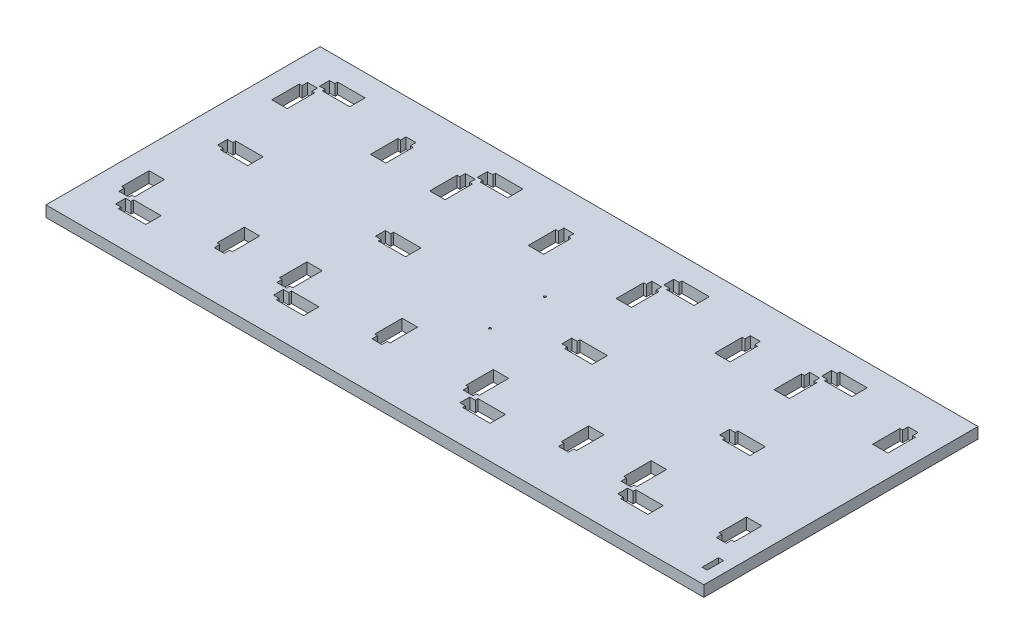
SolidWorks part; units mm, degrees
ref_plane "Front Plane" through (0, 0, 0) normal (0, 0, 1) x (1, 0, 0)
ref_plane "Top Plane" through (0, 0, 0) normal (0, 1, 0) x (1, 0, 0)
ref_plane "Right Plane" through (0, 0, 0) normal (1, 0, 0) x (0, 0, -1)
sketch "Sketch1" plane through (0, 0, 0) normal (0, 1, 0) x (1, 0, 0)
  line L0 (300, 0) -> (300, -250) construction
  line L1 (0, 0) -> (600, 0)
  line L2 (0, 0) -> (0, -250)
  line L3 (0, -250) -> (600, -250)
  line L4 (600, 0) -> (600, -250)
  line L5 (36, -113) -> (61, -113)
  line L6 (36, -20) -> (61, -20)
  line L8 (36, -34) -> (61, -34)
  line L9 (61, -20) -> (61, -34)
  line L11 (36, -127) -> (61, -127)
  line L12 (61, -113) -> (61, -127)
  line L13 (36, -206) -> (61, -206)
  line L15 (36, -220) -> (61, -220)
  line L16 (61, -206) -> (61, -220)
  line L19 (20, -39) -> (20, -64)
  line L20 (20, -64) -> (34, -64)
  line L21 (34, -39) -> (34, -64)
  line L22 (108, -37.0948) -> (108, -62.0948)
  line L23 (108, -62.0948) -> (122, -62.0948)
  line L24 (122, -37.0948) -> (122, -62.0948)
  line L25 (20, -176) -> (34, -176)
  line L26 (20, -176) -> (20, -201)
  line L28 (34, -176) -> (34, -203)
  line L29 (108, -177.0915) -> (122, -177.0915)
  line L30 (108, -177.0915) -> (108, -202.0915)
  line L32 (122, -177.0915) -> (122, -202.0915)
  line L61 (144, 0) -> (144, -250) construction
  line L62 (280, 0) -> (280, -250) construction
  line L75 (0, -20) -> (600, -20) construction
  line L92 (0, -220) -> (600, -220) construction
  line L93 (164, 0) -> (164, -250) construction
  line L150 (580, 0) -> (580, -250) construction
  line L151 (320, 0) -> (320, -250) construction
  line L152 (460, 0) -> (460, -250) construction
  line L153 (440, 0) -> (440, -250) construction
  line L194 (20, 0) -> (20, -250) construction
  line L263 (36, -20) -> (36, -22.5)
  line L272 (36, -22.5) -> (31, -22.5)
  line L273 (31, -22.5) -> (31, -31.5)
  line L274 (31, -31.5) -> (36, -31.5)
  line L275 (36, -31.5) -> (36, -34)
  line L276 (20, -39) -> (22.5, -39)
  line L277 (22.5, -39) -> (22.5, -34)
  line L278 (22.5, -34) -> (31.5, -34)
  line L279 (31.5, -34) -> (31.5, -39)
  line L280 (31.5, -39) -> (34, -39)
  line L281 (108, -37.0948) -> (110.5, -37.0948)
  line L282 (110.5, -37.0948) -> (110.5, -32.0948)
  line L283 (110.5, -32.0948) -> (119.5, -32.0948)
  line L284 (119.5, -32.0948) -> (119.5, -37.0948)
  line L285 (119.5, -37.0948) -> (122, -37.0948)
  line L286 (36, -113) -> (36, -115.5)
  line L287 (36, -115.5) -> (31, -115.5)
  line L288 (31, -115.5) -> (31, -124.5)
  line L289 (31, -124.5) -> (36, -124.5)
  line L290 (36, -124.5) -> (36, -127)
  line L291 (20, -201) -> (22.5, -201)
  line L292 (22.5, -201) -> (22.5, -206)
  line L293 (22.5, -206) -> (31.5, -206)
  line L294 (31.5, -206) -> (31.5, -203)
  line L295 (31.5, -203) -> (34, -203)
  line L296 (36, -206) -> (36, -208.5)
  line L297 (36, -208.5) -> (31, -208.5)
  line L298 (31, -208.5) -> (31, -217.5)
  line L299 (31, -217.5) -> (36, -217.5)
  line L300 (36, -217.5) -> (36, -220)
  line L301 (108, -202.0915) -> (110.5, -202.0915)
  line L302 (110.5, -202.0915) -> (110.5, -207.0915)
  line L303 (110.5, -207.0915) -> (119.5, -207.0915)
  line L304 (119.5, -207.0915) -> (119.5, -202.0915)
  line L305 (119.5, -202.0915) -> (122, -202.0915)
  line L306 (179.9626, -31.5) -> (179.9626, -34)
  line L307 (179.9626, -34) -> (204.9626, -34)
  line L308 (204.9626, -20) -> (204.9626, -34)
  line L309 (179.9626, -20) -> (204.9626, -20)
  line L310 (179.9626, -20) -> (179.9626, -22.5)
  line L311 (179.9626, -22.5) -> (174.9626, -22.5)
  line L312 (174.9626, -22.5) -> (174.9626, -31.5)
  line L313 (174.9626, -31.5) -> (179.9626, -31.5)
  line L314 (263.4626, -37.0948) -> (265.9626, -37.0948)
  line L315 (265.9626, -37.0948) -> (265.9626, -62.0948)
  line L316 (251.9626, -62.0948) -> (265.9626, -62.0948)
  line L317 (251.9626, -37.0948) -> (251.9626, -62.0948)
  line L318 (251.9626, -37.0948) -> (254.4626, -37.0948)
  line L319 (254.4626, -37.0948) -> (254.4626, -32.0948)
  line L320 (254.4626, -32.0948) -> (263.4626, -32.0948)
  line L321 (263.4626, -32.0948) -> (263.4626, -37.0948)
  line L322 (175.4626, -39) -> (177.9626, -39)
  line L323 (177.9626, -39) -> (177.9626, -64)
  line L324 (163.9626, -64) -> (177.9626, -64)
  line L325 (163.9626, -39) -> (163.9626, -64)
  line L326 (163.9626, -39) -> (166.4626, -39)
  line L327 (166.4626, -39) -> (166.4626, -34)
  line L328 (166.4626, -34) -> (175.4626, -34)
  line L329 (175.4626, -34) -> (175.4626, -39)
  line L330 (179.9626, -124.5) -> (179.9626, -127)
  line L331 (179.9626, -127) -> (204.9626, -127)
  line L332 (204.9626, -113) -> (204.9626, -127)
  line L333 (179.9626, -113) -> (204.9626, -113)
  line L334 (179.9626, -113) -> (179.9626, -115.5)
  line L335 (179.9626, -115.5) -> (174.9626, -115.5)
  line L336 (174.9626, -115.5) -> (174.9626, -124.5)
  line L337 (174.9626, -124.5) -> (179.9626, -124.5)
  line L338 (263.4626, -202.0915) -> (265.9626, -202.0915)
  line L339 (265.9626, -177.0915) -> (265.9626, -202.0915)
  line L340 (251.9626, -177.0915) -> (265.9626, -177.0915)
  line L341 (251.9626, -177.0915) -> (251.9626, -202.0915)
  line L342 (251.9626, -202.0915) -> (254.4626, -202.0915)
  line L343 (254.4626, -202.0915) -> (254.4626, -207.0915)
  line L344 (254.4626, -207.0915) -> (263.4626, -207.0915)
  line L345 (263.4626, -207.0915) -> (263.4626, -202.0915)
  line L346 (175.4626, -203) -> (177.9626, -203)
  line L347 (177.9626, -176) -> (177.9626, -203)
  line L348 (163.9626, -176) -> (177.9626, -176)
  line L349 (163.9626, -176) -> (163.9626, -201)
  line L350 (163.9626, -201) -> (166.4626, -201)
  line L351 (166.4626, -201) -> (166.4626, -206)
  line L352 (166.4626, -206) -> (175.4626, -206)
  line L353 (175.4626, -206) -> (175.4626, -203)
  line L354 (179.9626, -217.5) -> (179.9626, -220)
  line L355 (179.9626, -220) -> (204.9626, -220)
  line L356 (204.9626, -206) -> (204.9626, -220)
  line L357 (179.9626, -206) -> (204.9626, -206)
  line L358 (179.9626, -206) -> (179.9626, -208.5)
  line L359 (179.9626, -208.5) -> (174.9626, -208.5)
  line L360 (174.9626, -208.5) -> (174.9626, -217.5)
  line L361 (174.9626, -217.5) -> (179.9626, -217.5)
  line L474 (350, -31.5) -> (350, -34)
  line L478 (350, -34) -> (375, -34)
  line L479 (585.3518, -222) -> (590, -222)
  line L480 (585.3518, -222) -> (585.3518, -237)
  line L481 (585.3518, -237) -> (590, -237)
  line L482 (590, -222) -> (590, -237)
  line L483 (375, -20) -> (375, -34)
  line L484 (350, -20) -> (375, -20)
  line L485 (350, -20) -> (350, -22.5)
  line L486 (350, -22.5) -> (345, -22.5)
  line L487 (345, -22.5) -> (345, -31.5)
  line L488 (345, -31.5) -> (350, -31.5)
  line L489 (433.5, -37.0948) -> (436, -37.0948)
  line L490 (436, -37.0948) -> (436, -62.0948)
  line L491 (422, -62.0948) -> (436, -62.0948)
  line L492 (422, -37.0948) -> (422, -62.0948)
  line L493 (422, -37.0948) -> (424.5, -37.0948)
  line L494 (424.5, -37.0948) -> (424.5, -32.0948)
  line L495 (424.5, -32.0948) -> (433.5, -32.0948)
  line L496 (433.5, -32.0948) -> (433.5, -37.0948)
  line L497 (345.5, -39) -> (348, -39)
  line L498 (348, -39) -> (348, -64)
  line L499 (334, -64) -> (348, -64)
  line L500 (334, -39) -> (334, -64)
  line L501 (334, -39) -> (336.5, -39)
  line L502 (336.5, -39) -> (336.5, -34)
  line L503 (336.5, -34) -> (345.5, -34)
  line L504 (345.5, -34) -> (345.5, -39)
  line L505 (350, -124.5) -> (350, -127)
  line L506 (350, -127) -> (375, -127)
  line L507 (375, -113) -> (375, -127)
  line L508 (350, -113) -> (375, -113)
  line L509 (350, -113) -> (350, -115.5)
  line L510 (350, -115.5) -> (345, -115.5)
  line L511 (345, -115.5) -> (345, -124.5)
  line L512 (345, -124.5) -> (350, -124.5)
  line L513 (433.5, -202.0915) -> (436, -202.0915)
  line L514 (436, -177.0915) -> (436, -202.0915)
  line L515 (422, -177.0915) -> (436, -177.0915)
  line L516 (422, -177.0915) -> (422, -202.0915)
  line L517 (422, -202.0915) -> (424.5, -202.0915)
  line L518 (424.5, -202.0915) -> (424.5, -207.0915)
  line L519 (424.5, -207.0915) -> (433.5, -207.0915)
  line L520 (433.5, -207.0915) -> (433.5, -202.0915)
  line L521 (345.5, -203) -> (348, -203)
  line L522 (348, -176) -> (348, -203)
  line L523 (334, -176) -> (348, -176)
  line L524 (334, -176) -> (334, -201)
  line L525 (334, -201) -> (336.5, -201)
  line L526 (336.5, -201) -> (336.5, -206)
  line L527 (336.5, -206) -> (345.5, -206)
  line L528 (345.5, -206) -> (345.5, -203)
  line L529 (350, -217.5) -> (350, -220)
  line L530 (350, -220) -> (375, -220)
  line L531 (375, -206) -> (375, -220)
  line L532 (350, -206) -> (375, -206)
  line L533 (350, -206) -> (350, -208.5)
  line L534 (350, -208.5) -> (345, -208.5)
  line L535 (345, -208.5) -> (345, -217.5)
  line L536 (345, -217.5) -> (350, -217.5)
  line L537 (489.4626, -203) -> (491.9626, -203)
  line L538 (491.9626, -176) -> (491.9626, -203)
  line L539 (477.9626, -176) -> (491.9626, -176)
  line L540 (477.9626, -176) -> (477.9626, -201)
  line L541 (477.9626, -201) -> (480.4626, -201)
  line L542 (480.4626, -201) -> (480.4626, -206)
  line L543 (480.4626, -206) -> (489.4626, -206)
  line L544 (489.4626, -206) -> (489.4626, -203)
  line L545 (493.9626, -217.5) -> (493.9626, -220)
  line L546 (493.9626, -220) -> (518.9626, -220)
  line L547 (518.9626, -206) -> (518.9626, -220)
  line L548 (493.9626, -206) -> (518.9626, -206)
  line L549 (493.9626, -206) -> (493.9626, -208.5)
  line L550 (493.9626, -208.5) -> (488.9626, -208.5)
  line L551 (488.9626, -208.5) -> (488.9626, -217.5)
  line L552 (488.9626, -217.5) -> (493.9626, -217.5)
  line L553 (577.4626, -202.0915) -> (579.9626, -202.0915)
  line L554 (579.9626, -177.0915) -> (579.9626, -202.0915)
  line L555 (565.9626, -177.0915) -> (579.9626, -177.0915)
  line L556 (565.9626, -177.0915) -> (565.9626, -202.0915)
  line L557 (565.9626, -202.0915) -> (568.4626, -202.0915)
  line L558 (568.4626, -202.0915) -> (568.4626, -207.0915)
  line L559 (568.4626, -207.0915) -> (577.4626, -207.0915)
  line L560 (577.4626, -207.0915) -> (577.4626, -202.0915)
  line L561 (493.9626, -124.5) -> (493.9626, -127)
  line L562 (493.9626, -127) -> (518.9626, -127)
  line L563 (518.9626, -113) -> (518.9626, -127)
  line L564 (493.9626, -113) -> (518.9626, -113)
  line L565 (493.9626, -113) -> (493.9626, -115.5)
  line L566 (493.9626, -115.5) -> (488.9626, -115.5)
  line L567 (488.9626, -115.5) -> (488.9626, -124.5)
  line L568 (488.9626, -124.5) -> (493.9626, -124.5)
  line L569 (489.4626, -39) -> (491.9626, -39)
  line L570 (491.9626, -39) -> (491.9626, -64)
  line L571 (477.9626, -64) -> (491.9626, -64)
  line L572 (477.9626, -39) -> (477.9626, -64)
  line L573 (477.9626, -39) -> (480.4626, -39)
  line L574 (480.4626, -39) -> (480.4626, -34)
  line L575 (480.4626, -34) -> (489.4626, -34)
  line L576 (489.4626, -34) -> (489.4626, -39)
  line L577 (493.9626, -31.5) -> (493.9626, -34)
  line L578 (493.9626, -34) -> (518.9626, -34)
  line L579 (518.9626, -20) -> (518.9626, -34)
  line L580 (493.9626, -20) -> (518.9626, -20)
  line L581 (493.9626, -20) -> (493.9626, -22.5)
  line L582 (493.9626, -22.5) -> (488.9626, -22.5)
  line L583 (488.9626, -22.5) -> (488.9626, -31.5)
  line L584 (488.9626, -31.5) -> (493.9626, -31.5)
  line L585 (577.4626, -37.0948) -> (579.9626, -37.0948)
  line L586 (579.9626, -37.0948) -> (579.9626, -62.0948)
  line L587 (565.9626, -62.0948) -> (579.9626, -62.0948)
  line L588 (565.9626, -37.0948) -> (565.9626, -62.0948)
  line L589 (565.9626, -37.0948) -> (568.4626, -37.0948)
  line L590 (568.4626, -37.0948) -> (568.4626, -32.0948)
  line L591 (568.4626, -32.0948) -> (577.4626, -32.0948)
  line L592 (577.4626, -32.0948) -> (577.4626, -37.0948)
  circle A0 centre (300, -95) radius 1
  circle A1 centre (300, -145) radius 1
  point P27 (108, -49.5948)
  point P67 (109.25, -202.0915)
  point P263 (300, -120)
  dimension "D54" = 2
  dimension "D55" = 2
  dimension "D1" = 250
  dimension "D2" = 600
  dimension "D3" = 25
  dimension "D4" = 14
  dimension "D7" = 79
  dimension "D8" = 79
  dimension "D9" = 20
  dimension "D10" = 14
  dimension "D11" = 25
  dimension "D12" = 14
  dimension "D13" = 25
  dimension "D14" = 20
  dimension "D15" = 5
  dimension "D16" = 74
  dimension "D17" = 2
  dimension "D18" = 2.5
  dimension "D19" = 25
  dimension "D20" = 14
  dimension "D21" = 14
  dimension "D22" = 25
  dimension "D23" = 14
  dimension "D24" = 74
  dimension "D25" = 10
  dimension "D26" = 14
  dimension "D27" = 25
  dimension "D28" = 36
  dimension "D29" = 25
  dimension "D30" = 36
  dimension "D31" = 49
  dimension "D32" = 20
  dimension "D33" = 36
  dimension "D34" = 2.5
  dimension "D35" = 2.5
  dimension "D36" = 2.5
  dimension "D37" = 2.5
  dimension "D38" = 5
  dimension "D39" = 5
  dimension "D40" = 2.5
  dimension "D41" = 2.5
  dimension "D42" = 5
  dimension "D43" = 2.5
  dimension "D44" = 2.5
  dimension "D45" = 5
  dimension "D46" = 2.5
  dimension "D47" = 5
  dimension "D48" = 2.5
  dimension "D49" = 2.5
  dimension "D50" = 5
  dimension "D51" = 2.5
  dimension "D52" = 2.5
  dimension "D53" = 5
  dimension "D56" = 25
  dimension "D57" = 25
  dimension "D58" = 2
  dimension "D59" = 15
  dimension "D60" = 49
  dimension "D61" = 20
  dimension "D62" = 20
  dimension "D63" = 20
  dimension "D64" = 20
  dimension "D65" = 140
  dimension "D66" = 140
  dimension "D67" = 2
  dimension "D68" = 47
  dimension "D69" = 47
  dimension "D70" = 25
extrude "Boss-Extrude3" add sketch "Sketch1" along normal blind 10
